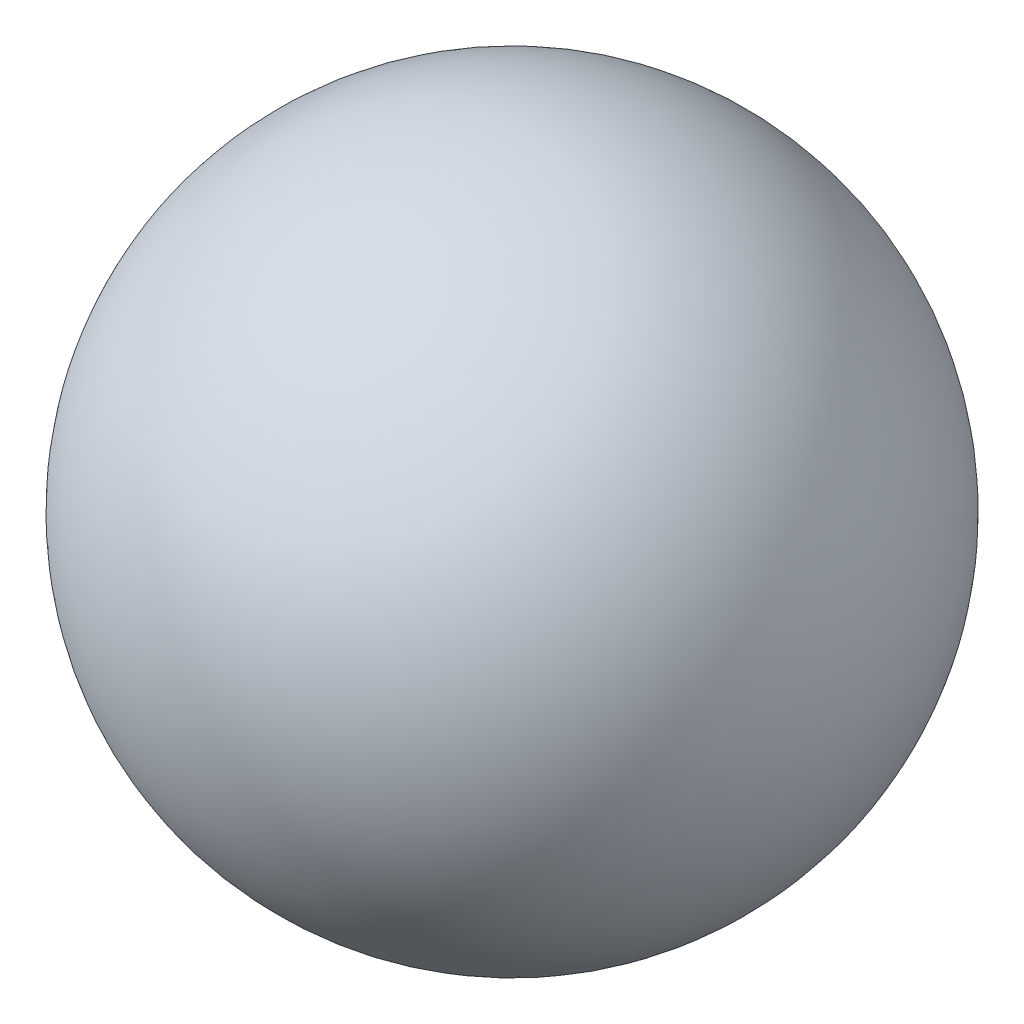
SolidWorks part; units mm, degrees
material "Chrome Stainless Steel"
ref_plane "Front Plane" through (0, 0, 0) normal (0, 0, 1) x (1, 0, 0)
ref_plane "Top Plane" through (0, 0, 0) normal (0, 1, 0) x (1, 0, 0)
ref_plane "Right Plane" through (0, 0, 0) normal (1, 0, 0) x (0, 0, -1)
sketch "Ball Bearing Sketch" plane through (0, 0, 0) normal (0, 0, 1) x (1, 0, 0)
  line L0 (0.7, 0) -> (-0.7, 0) construction
  line L1 (0.7, 0) -> (-0.7, 0)
  arc A0 (0.7, 0) -> (-0.7, 0) centre (0, 0) ccw
  dimension "Dia" = 1.4
revolve "Ball Bearing Revolve" add sketch "Ball Bearing Sketch" angle 360 about L0
